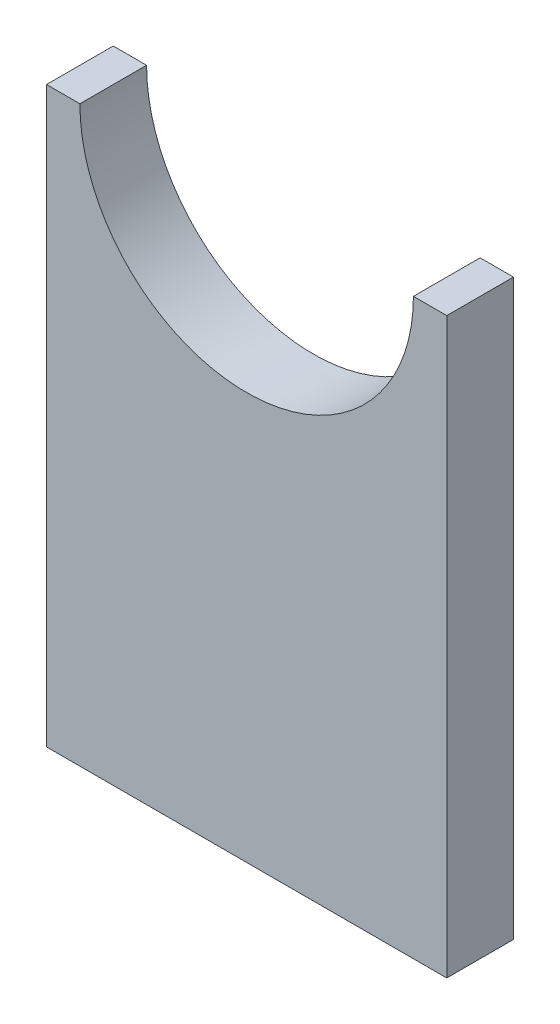
SolidWorks part; units mm, degrees
ref_plane "Front Plane" through (0, 0, 0) normal (0, 0, 1) x (1, 0, 0)
ref_plane "Top Plane" through (0, 0, 0) normal (0, 1, 0) x (1, 0, 0)
ref_plane "Right Plane" through (0, 0, 0) normal (1, 0, 0) x (0, 0, -1)
sketch "Sketch2" plane through (0, 0, 0) normal (0, 0, 1) x (1, 0, 0)
  line L1 (-15, 21.5) -> (15, 21.5)
  line L2 (-15, 21.5) -> (-15, -21.5)
  line L3 (-15, -21.5) -> (15, -21.5)
  line L4 (15, 21.5) -> (15, -21.5)
  line L5 (-15, 21.5) -> (15, -21.5) construction
  line L6 (-15, -21.5) -> (15, 21.5) construction
  point P0 (0, 0)
  dimension "D1" = 43
  dimension "D2" = 30
extrude "Boss-Extrude2" add sketch "Sketch2" along normal blind 5
sketch "Sketch3" plane through (0, 0, 0) normal (0, 0, -1) x (-1, 0, 0)
  line L0 (0, 0) -> (0, 43) construction
  line L1 (-15, 21.5) -> (15, 21.5) construction
  circle A0 centre (0, 21.5) radius 12.5
  dimension "D1" = 25
extrude "Cut-Extrude1" cut sketch "Sketch3" against normal through all
